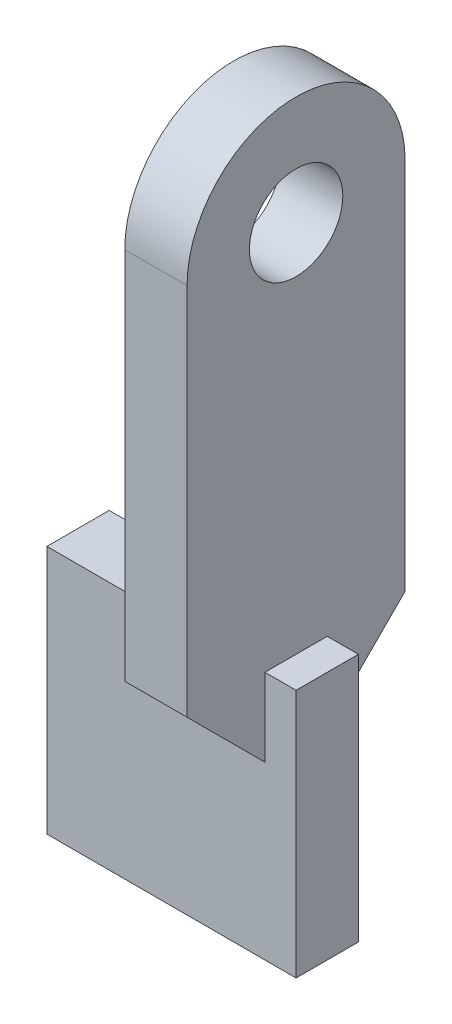
SolidWorks part; units mm, degrees
ref_plane "Front Plane" through (0, 0, 0) normal (0, 0, 1) x (1, 0, 0)
ref_plane "Top Plane" through (0, 0, 0) normal (0, 1, 0) x (1, 0, 0)
ref_plane "Right Plane" through (0, 0, 0) normal (1, 0, 0) x (0, 0, -1)
sketch "Sketch1" plane through (0, 0, 0) normal (1, 0, 0) x (0, 0, -1)
  line L0 (-3.5, 0) -> (-3.5, -12)
  line L1 (-3.5, -12) -> (3.5, -12)
  line L2 (3.5, -12) -> (3.5, 0)
  circle A0 centre (0, 0) radius 1.5
  arc A3 (3.5, 0) -> (-3.5, 0) centre (0, 0) ccw
  point P3 (0, -0.1493)
  dimension "D1" = 3
  dimension "D2" = 7
  dimension "D3" = 12
extrude "Boss-Extrude1" add sketch "Sketch1" along normal mid plane 2
sketch "Sketch2" plane through (0, 0, 0) normal (0, 0, 1) x (1, 0, 0)
  line L0 (1, -12) -> (-1, -12) construction
  line L2 (-2, 1.2325) -> (-2, -6.5855) construction
  line L3 (-6, -12) -> (2, -12)
  line L4 (-6, -12) -> (-6, -20)
  line L5 (-6, -20) -> (2, -20)
  line L6 (2, -12) -> (2, -20)
  point P4 (-2, -12)
  dimension "D1" = 2
  dimension "D2" = 8
  dimension "D3" = 8
extrude "Boss-Extrude2" add sketch "Sketch2" along normal mid plane 2
sketch "Sketch3" plane through (0, 0, 0) normal (1, 0, 0) x (0, 0, -1)
  line L0 (-3.5, -12) -> (-1, -14.5)
  line L1 (-1, -20) -> (-1, -12) construction
  line L2 (-3.5, -12) -> (-1, -12) construction
  line L3 (0, -12) -> (0, -3.0866) construction
  line L4 (-1, -12) -> (1, -12) construction
  line L5 (-1, -14.5) -> (-1, -12)
  line L6 (-1, -12) -> (-3.5, -12)
  line L7 (1, -12) -> (3.5, -12)
  line L8 (1, -14.5) -> (1, -12)
  line L9 (3.5, -12) -> (1, -14.5)
  dimension "D1" = 45
extrude "Boss-Extrude3" add sketch "Sketch3" along normal mid plane 2
